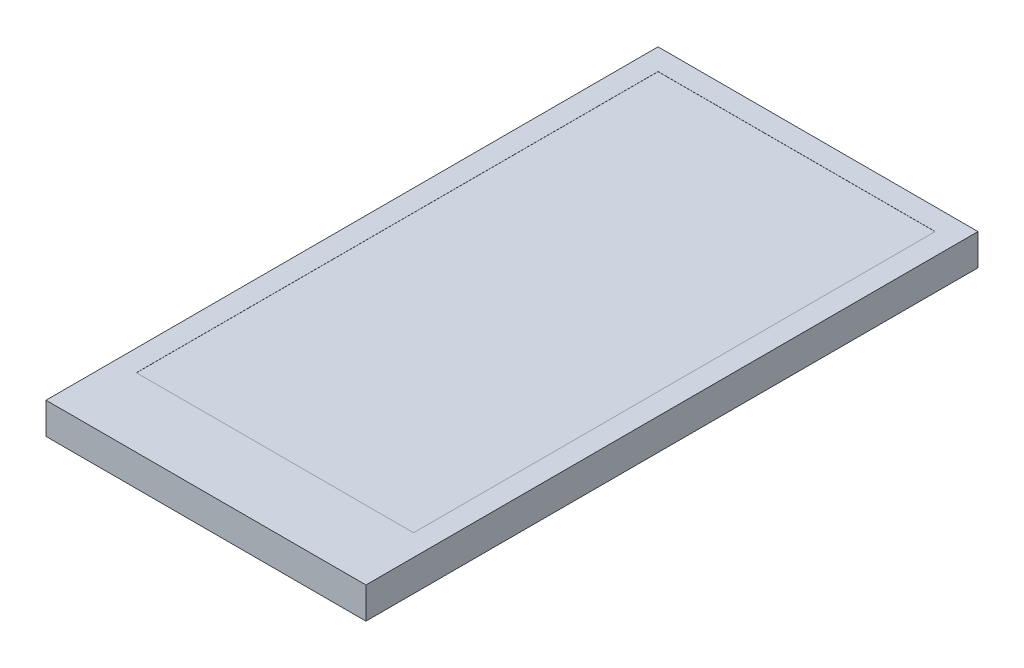
SolidWorks part; units mm, degrees
ref_plane "前视基准面" through (0, 0, 0) normal (0, 0, 1) x (1, 0, 0)
ref_plane "上视基准面" through (0, 0, 0) normal (0, 1, 0) x (1, 0, 0)
ref_plane "右视基准面" through (0, 0, 0) normal (1, 0, 0) x (0, 0, -1)
other "Configuration Table"
sketch "草图1" plane through (0, 0, 0) normal (0, 1, 0) x (1, 0, 0)
  line L0 (49.0742, 0) -> (75.2742, 0)
  line L1 (75.2742, 0) -> (75.2742, -50.12)
  line L2 (75.2742, -50.12) -> (49.0742, -50.12)
  line L3 (49.0742, -50.12) -> (49.0742, 0)
extrude "凸台-拉伸1" add sketch "草图1" along normal blind 2.57
sketch "草图2" plane through (0, 2.57, 0) normal (0, 1, 0) x (1, 0, 0)
  line L3 (50.8242, -1.75) -> (73.5242, -1.75)
  line L4 (73.5242, -1.75) -> (73.5242, -44.47)
  line L5 (73.5242, -44.47) -> (50.8242, -44.47)
  line L6 (50.8242, -44.47) -> (50.8242, -1.75)
extrude "切除-拉伸1" cut sketch "草图2" against normal blind 0.01
